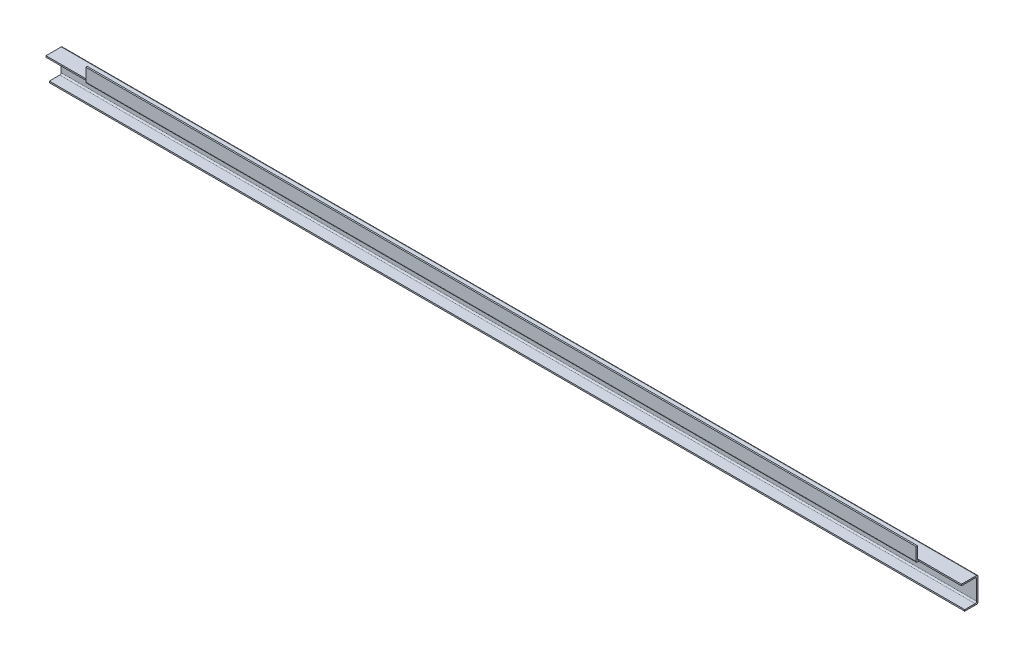
SolidWorks part; units mm, degrees
ref_plane "Front Plane" through (0, 0, 0) normal (0, 0, 1) x (1, 0, 0)
ref_plane "Top Plane" through (0, 0, 0) normal (0, 1, 0) x (1, 0, 0)
ref_plane "Right Plane" through (0, 0, 0) normal (1, 0, 0) x (0, 0, -1)
sketch "Sketch1" plane through (0, 0, 0) normal (1, 0, 0) x (0, 0, -1)
  line L0 (0, 0) -> (25, 0)
  line L1 (25, 0) -> (25, 47)
  line L2 (25, 47) -> (-13, 47)
  line L3 (-13, 47) -> (-13, 77)
  line L4 (0, -3) -> (28, -3)
  line L5 (28, -3) -> (28, 50)
  line L6 (28, 50) -> (-10, 50)
  line L7 (-10, 50) -> (-10, 77)
  line L8 (0, 0) -> (0, -3)
  line L9 (-13, 77) -> (-10, 77)
  dimension "D1" = 3
  dimension "D2" = 27
  dimension "D3" = 53
  dimension "D4" = 38
  dimension "D5" = 28
extrude "Boss-Extrude1" add sketch "Sketch1" along normal blind 1934
fillet "Fillet1" radius 3 6 edges at (967, -3, -28) (967, 50, -28) (967, 50, 10) (967, 0, -25) (967, 47, -25) (967, 47, 13)
sketch "Sketch2" plane through (0, 0, 13) normal (0, 0, 1) x (1, 0, 0)
  line L0 (0, 77) -> (90, 77)
  line L1 (1934, 77) -> (0, 77) construction
  line L2 (90, 77) -> (90, 47)
  line L3 (0, 47) -> (1934, 47) construction
  line L4 (90, 47) -> (0, 47)
  line L5 (0, 47) -> (0, 44) construction
  line L6 (0, 47) -> (0, 77)
  dimension "D1" = 90
extrude "Cut-Extrude1" cut sketch "Sketch2" against normal blind 6
sketch "Sketch3" plane through (0, 0, 13) normal (0, 0, 1) x (1, 0, 0)
  line L0 (1934, 77) -> (1844, 77)
  line L1 (1844, 77) -> (1844, 47)
  line L2 (0, 47) -> (1934, 47) construction
  line L3 (1844, 47) -> (1934, 47)
  line L4 (1934, 47) -> (1934, 77)
  dimension "D1" = 90
extrude "Cut-Extrude2" cut sketch "Sketch3" against normal blind 6
equation "\"side_door_bottom_R_3mm_length\"=1934.0"
equation "\"D1@Boss-Extrude1\"=\"side_door_bottom_R_3mm_length\""
equation "\"D1@Cut-Extrude1\"=\"side_door_bottom_R_3mm_Cut_RF_length\""
equation "\"D1@Sketch2\" = IIF ( ( \"DoorSeparator_RF_3mm_withHinge_exist\" ) = 1 , 90 , 30 )"
equation "\"D1@Sketch3\" = IIF ( ( \"DoorSeparator_RB_3mm_withHinge_exist\" ) = 1 , 90 , 30 )"
equation "\"CarBeamWidth\"=700.0"
equation "\"WheelWidth\"=650.0"
equation "\"Wheel_FrontBoxDistance\"=1390.0"
equation "\"MetalSheet_3mm_length\"=5030.0"
equation "\"MetalSheet_3mm_width\"=1923.0"
equation "\"MetalSheet_3mm_FloorCut_L_length\"=1764.0"
equation "\"MetalSheet_3mm_FloorCut_L_disdance\"=1665.0"
equation "\"MetalSheet_3mm_FloorCut_R_length\"=1764.0"
equation "\"MetalSheet_3mm_FloorCut_R_disdance\"=1665.0"
equation "\"indoorHeight\"=1940.0"
equation "\"haveDoor_R\"=1"
equation "\"1Bar_Side_RF_3mm_length\"=1493.0"
equation "\"1Bar_Side_RB_3mm_length\"=1493.0"
equation "\"DoorSeparator_RF_3mm_withHinge_toFrontDistance\"=1673.0"
equation "\"DoorSeparator_RF_3mm_withHinge_exist\"=1"
equation "\"DoorSeparator_RB_3mm_withHinge_toFrontDistance\"=3427.0"
equation "\"DoorSeparator_RB_3mm_withHinge_exist\"=1"
equation "\"Door_R1_L_open_Single_toFrontDistance\"=2547.5"
equation "\"Door_R1_L_open_Single_exist\"=1"
equation "\"Door_R1_R_open_Single_toFrontDistance\"=3422.0"
equation "\"Door_R1_R_open_Single_exist\"=1"
equation "\"x\"=66.0"
equation "\"da\"=62.0"
equation "\"SquareTube_length\"=1923.0"
equation "\"channelSteel_length\"=5030.0"
equation "\"SquareTube_inFront_AvgDistance\"=285.0"
equation "\"SquareTube_inFront_TotalCount\"=5"
equation "\"SquareTube_inFront1_cutDepth50_R\"=0.5"
equation "\"SquareTube_inFront1_cutDepth50_L\"=0.5"
equation "\"SquareTube_inFront2_cutDepth50_R\"=0.5"
equation "\"SquareTube_inFront2_cutDepth50_L\"=0.5"
equation "\"SquareTube_inFront3_cutDepth50_R\"=0.5"
equation "\"SquareTube_inFront3_cutDepth50_L\"=0.5"
equation "\"SquareTube_inFront4_cutDepth50_R\"=0.5"
equation "\"SquareTube_inFront4_cutDepth50_L\"=0.5"
equation "\"SquareTube_inFront5_cutDepth50_R\"=50"
equation "\"SquareTube_inFront5_cutDepth50_L\"=50"
equation "\"SquareTube_inFront6_cutDepth50_R\"=50"
equation "\"SquareTube_inFront6_cutDepth50_L\"=50"
equation "\"SquareTube_inFront7_cutDepth50_R\"=50"
equation "\"SquareTube_inFront7_cutDepth50_L\"=50"
equation "\"SquareTube_inFront8_cutDepth50_R\"=50"
equation "\"SquareTube_inFront8_cutDepth50_L\"=50"
equation "\"SquareTube_inFront9_cutDepth50_R\"=50"
equation "\"SquareTube_inFront9_cutDepth50_L\"=50"
equation "\"SquareTube_inFront10_cutDepth50_R\"=50"
equation "\"SquareTube_inFront10_cutDepth50_L\"=50"
equation "\"SquareTube_inFront11_cutDepth50_R\"=50"
equation "\"SquareTube_inFront11_cutDepth50_L\"=50"
equation "\"SquareTube_inFront12_cutDepth50_R\"=50"
equation "\"SquareTube_inFront12_cutDepth50_L\"=50"
equation "\"SquareTube_inFront13_cutDepth50_R\"=50"
equation "\"SquareTube_inFront13_cutDepth50_L\"=50"
equation "\"SquareTube_inFront14_cutDepth50_R\"=50"
equation "\"SquareTube_inFront14_cutDepth50_L\"=50"
equation "\"SquareTube_inBack_AvgDistance\"=333.125"
equation "\"SquareTube_inBack_TotalCount\"=9"
equation "\"SquareTube_inBack1_cutDepth50_R\"=50"
equation "\"SquareTube_inBack1_cutDepth50_L\"=50"
equation "\"SquareTube_inBack2_cutDepth50_R\"=50"
equation "\"SquareTube_inBack2_cutDepth50_L\"=50"
equation "\"SquareTube_inBack3_cutDepth50_R\"=50"
equation "\"SquareTube_inBack3_cutDepth50_L\"=50"
equation "\"SquareTube_inBack4_cutDepth50_R\"=50"
equation "\"SquareTube_inBack4_cutDepth50_L\"=50"
equation "\"SquareTube_inBack5_cutDepth50_R\"=50"
equation "\"SquareTube_inBack5_cutDepth50_L\"=50"
equation "\"SquareTube_inBack6_cutDepth50_R\"=0.5"
equation "\"SquareTube_inBack6_cutDepth50_L\"=0.5"
equation "\"SquareTube_inBack7_cutDepth50_R\"=0.5"
equation "\"SquareTube_inBack7_cutDepth50_L\"=0.5"
equation "\"SquareTube_inBack8_cutDepth50_R\"=0.5"
equation "\"SquareTube_inBack8_cutDepth50_L\"=0.5"
